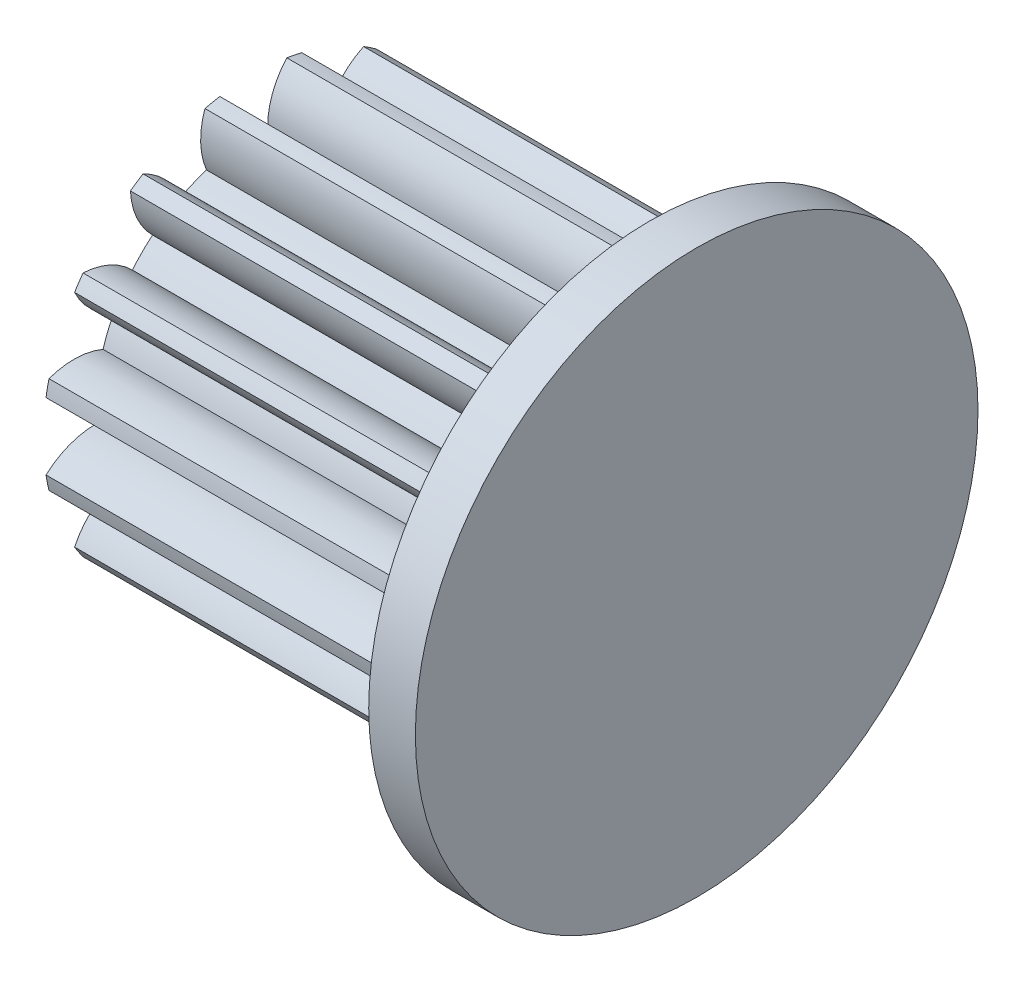
SolidWorks part; units mm, degrees
ref_plane "Plane1" through (0, 0, 0) normal (0, 0, 1) x (1, 0, 0)
ref_plane "Plane2" through (0, 0, 0) normal (0, 1, 0) x (1, 0, 0)
ref_plane "Plane3" through (0, 0, 0) normal (1, 0, 0) x (0, 0, -1)
sketch "HoldingSke" plane through (0, 0, 0) normal (0, 1, 0) x (1, 0, 0)
  line L0 (0, 0) -> (1.9225, -0.5513)
  line L1 (-15, 0) -> (100, 0) construction
  line L2 (0, 0) -> (-2.1039, 2.3779)
  line L3 (0, 0) -> (-11.863, 4.5341)
  line L4 (0, 0) -> (8.3015, 2.3804)
  line L5 (0, 0) -> (-46.8476, -17.4728)
  line L6 (0, 0) -> (-6.2172, -4.1948)
  line L7 (-2.1039, 2.3779) -> (8.6586, 51.2059)
  line L8 (-76.2, 54.61) -> (-75.3, 54.61)
  line L9 (-67.7845, 28.3722) -> (-49.3413, 33.142)
  line L10 (-76.2, 71.12) -> (104.1128, 71.12)
  line L11 (0, 0) -> (-7.5, 0)
  line L12 (-76.2, 101.6) -> (-76.181, 101.6)
  line L13 (24.9733, 27.94) -> (52.9518, 28.4284)
  line L14 (24.9733, 27.94) -> (24.9743, 27.94)
  line L15 (24.9733, 27.94) -> (100.4006, 29.5858)
  line L16 (-63.627, -0.5) -> (-12.827, -0.5)
  circle A0 centre (0, 0) radius 2.5
  circle A1 centre (0, 0) radius 3.374
  circle A2 centre (0, 0) radius 37.5
  circle A3 centre (0, 0) radius 2.5
  dimension "MHD" = 6.748
  dimension "Hub_dia" = 75
  dimension "Bore" = 5
  dimension "MBD" = 5
  dimension "Num_teeth" = 16
  dimension "Pitch" = 2
  dimension "Overall_len" = 50
  dimension "Show_teeth" = 16
  dimension "Thickness" = 7.5
  dimension "OAL" = 50.0001
  dimension "T_dim" = 0.9
  dimension "Ap" = 14.5
  dimension "H" = 19.05
  dimension "Pitch_radius" = 180.3128
  dimension "Width" = 7.5
  dimension "Backlash" = 0.019
  dimension "Addendum_fac" = 1
  dimension "Dedendum_fac" = 1.25
  dimension "Clearance_fac" = 0.25
  dimension "Dedendum_add" = 0.001
  dimension "Module" = 0.5
sketch "BasProSke" plane through (0, 0, 0) normal (0, 1, 0) x (1, 0, 0)
  line L0 (-10, 0) -> (60, 0) construction
  line L1 (0, 0) -> (0, 4.5)
  line L2 (0, 0) -> (7.5, 0)
  line L3 (7.5, 0) -> (7.5, 4.5)
  line L4 (7.5, 4.5) -> (0, 4.5)
  dimension "Thickness" = 7.5
  dimension "Diameter" = 9
revolve "Base-Revolve" add sketch "BasProSke" angle 360 about L0
sketch "TooCutSke" plane through (0, 0, 0) normal (1, 0, 0) x (0, 0, -1)
  line L1 (0, 0) -> (0, 107) construction
  line L2 (0, 0) -> (-0.4253, 3.9773) construction
  line L3 (0, 0) -> (-1.5544, 7.8146) construction
  line L4 (-0.4253, 3.9773) -> (-0.7772, 3.9073) construction
  arc A0 (0.306, 3.3601) -> (-0.306, 3.3601) centre (0, 0) ccw
  arc A1 (0.7382, 4.4648) -> (-0.7382, 4.4648) centre (0, 0) ccw
  circle A2 centre (0, 0) radius 4 construction
  circle A3 centre (0, 0) radius 3.8726 construction
  arc A4 (-0.306, 3.3601) -> (-0.7382, 4.4648) centre (-1.906, 3.3711) ccw
  arc A5 (0.7382, 4.4648) -> (0.306, 3.3601) centre (1.906, 3.3711) ccw
  dimension "Root_dia" = 6.748
  dimension "Overcut_dia" = 9.0508
  dimension "Pitch_dia" = 8
  dimension "Base_dia" = 7.7452
  dimension "Flank_rad" = 1.6
  dimension "Half_ang" = 11.25
  dimension "Half_CT" = 0.3588
extrude "ToothCut" cut sketch "TooCutSke" along normal through all
fillet "Breaks" [suppressed] radius 0.01
fillet "RootFillets" [suppressed] radius 0.126
pattern_circular "TeethCuts" count 16 every 22.5 about axis through (-10, 0, 0) along (1, 0, 0) of "ToothCut", "RootFillets", "Breaks"
sketch "HubNeaOneSke" plane through (0, 0, 0) normal (-1, 0, 0) x (0, 0, 1)
  circle A0 centre (0, 0) radius 3.374
  dimension "Diameter" = 6.748
extrude "HubNearOne" [suppressed] add sketch "HubNeaOneSke" along normal blind 42.5001
sketch "HubNeaBotSke" plane through (0, 0, 0) normal (-1, 0, 0) x (0, 0, 1)
  circle A0 centre (0, 0) radius 3.374
  dimension "Diameter" = 6.748
extrude "HubNearBoth" [suppressed] add sketch "HubNeaBotSke" along normal blind 21.25
ref_plane "FarPln" through (7.5, 0, 0) normal (1, 0, 0) x (0, 0, -1)
sketch "HubFarSke" plane through (7.5, 0, 0) normal (1, 0, 0) x (0, 0, -1)
  circle A0 centre (0, 0) radius 3.374
  dimension "Diameter" = 6.748
extrude "HubFar" [suppressed] add sketch "HubFarSke" along normal blind 21.25
sketch "BorSke" plane through (0, 0, 0) normal (1, 0, 0) x (0, 0, -1)
  circle A0 centre (0, 0) radius 2.5
  dimension "Diameter" = 5
extrude "Bore" cut sketch "BorSke" along normal mid plane 100.0001
sketch "KeySke" plane through (0, 0, 0) normal (1, 0, 0) x (0, 0, -1)
  line L0 (-1, 0) -> (-1, 3.4)
  line L1 (-1, 3.4) -> (1, 3.4)
  line L2 (1, 3.4) -> (1, 0)
  line L3 (0, 0) -> (0, 34) construction
  line L4 (-1, 0) -> (1, 0)
  dimension "Offset" = 3.4
  dimension "Width" = 2
extrude "Keyway" [suppressed] cut sketch "KeySke" along normal mid plane 100.0001
pattern_circular "Keyway2" [suppressed] count 2 every 90 about axis through (-10, 0, 0) along (1, 0, 0)
sketch "Esquisse5" plane through (7.5, 0, 0) normal (1, 0, 0) x (0, 0, -1)
  circle A0 centre (0, 0) radius 2.85
  circle A1 centre (0, 0) radius 6.0278
extrude "Boss.-Extru.4" add sketch "Esquisse5" along normal blind 1
sketch "Esquisse7" plane through (0, 0, 0) normal (-1, 0, 0) x (0, 0, 1)
  circle A0 centre (0, 0) radius 3.0071
extrude "Boss.-Extru.6" add sketch "Esquisse7" along normal up to surface (8.5 mm away)
sketch "Esquisse8" plane through (0, 0, 0) normal (-1, 0, 0) x (0, 0, 1)
  arc A128 (3.3601, 0.306) -> (4.4424, 0.7176) centre (3.3711, 1.906) ccw
  arc A129 (4.4424, 0.7176) -> (4.3789, 1.0371) centre (0, 0) ccw
  arc A130 (4.3789, 1.0371) -> (3.2214, 1.0031) centre (3.8439, -0.4708) ccw
  arc A131 (3.2214, 1.0031) -> (2.9872, 1.5686) centre (0, 0) ccw
  arc A132 (2.9872, 1.5686) -> (3.8296, 2.363) centre (2.3851, 3.051) ccw
  arc A133 (3.8296, 2.363) -> (3.6487, 2.6338) centre (0, 0) ccw
  arc A134 (3.6487, 2.6338) -> (2.5923, 2.1596) centre (3.7314, 1.036) ccw
  arc A135 (2.5923, 2.1596) -> (2.1596, 2.5923) centre (0, 0) ccw
  arc A136 (2.1596, 2.5923) -> (2.6338, 3.6487) centre (1.036, 3.7314) ccw
  arc A137 (2.6338, 3.6487) -> (2.363, 3.8296) centre (0, 0) ccw
  arc A138 (2.363, 3.8296) -> (1.5686, 2.9872) centre (3.051, 2.3851) ccw
  arc A139 (1.5686, 2.9872) -> (1.0031, 3.2214) centre (0, 0) ccw
  arc A140 (1.0031, 3.2214) -> (1.0371, 4.3789) centre (-0.4708, 3.8439) ccw
  arc A141 (1.0371, 4.3789) -> (0.7176, 4.4424) centre (0, 0) ccw
  arc A142 (0.7176, 4.4424) -> (0.306, 3.3601) centre (1.906, 3.3711) ccw
  arc A143 (0.306, 3.3601) -> (-0.306, 3.3601) centre (0, 0) ccw
  arc A144 (-0.306, 3.3601) -> (-0.7176, 4.4424) centre (-1.906, 3.3711) ccw
  arc A145 (-0.7176, 4.4424) -> (-1.0371, 4.3789) centre (0, 0) ccw
  arc A146 (-1.0371, 4.3789) -> (-1.0031, 3.2214) centre (0.4708, 3.8439) ccw
  arc A147 (-1.0031, 3.2214) -> (-1.5686, 2.9872) centre (0, 0) ccw
  arc A148 (-1.5686, 2.9872) -> (-2.363, 3.8296) centre (-3.051, 2.3851) ccw
  arc A149 (-2.363, 3.8296) -> (-2.6338, 3.6487) centre (0, 0) ccw
  arc A150 (-2.6338, 3.6487) -> (-2.1596, 2.5923) centre (-1.036, 3.7314) ccw
  arc A151 (-2.1596, 2.5923) -> (-2.5923, 2.1596) centre (0, 0) ccw
  arc A152 (-2.5923, 2.1596) -> (-3.6487, 2.6338) centre (-3.7314, 1.036) ccw
  arc A153 (-3.6487, 2.6338) -> (-3.8296, 2.363) centre (0, 0) ccw
  arc A154 (-3.8296, 2.363) -> (-2.9872, 1.5686) centre (-2.3851, 3.051) ccw
  arc A155 (-2.9872, 1.5686) -> (-3.2214, 1.0031) centre (0, 0) ccw
  arc A156 (-3.2214, 1.0031) -> (-4.3789, 1.0371) centre (-3.8439, -0.4708) ccw
  arc A157 (-4.3789, 1.0371) -> (-4.4424, 0.7176) centre (0, 0) ccw
  arc A158 (-4.4424, 0.7176) -> (-3.3601, 0.306) centre (-3.3711, 1.906) ccw
  arc A159 (-3.3601, 0.306) -> (-3.3601, -0.306) centre (0, 0) ccw
  arc A160 (-3.3601, -0.306) -> (-4.4424, -0.7176) centre (-3.3711, -1.906) ccw
  arc A161 (-4.4424, -0.7176) -> (-4.3789, -1.0371) centre (0, 0) ccw
  arc A162 (-4.3789, -1.0371) -> (-3.2214, -1.0031) centre (-3.8439, 0.4708) ccw
  arc A163 (-3.2214, -1.0031) -> (-2.9872, -1.5686) centre (0, 0) ccw
  arc A164 (-2.9872, -1.5686) -> (-3.8296, -2.363) centre (-2.3851, -3.051) ccw
  arc A165 (-3.8296, -2.363) -> (-3.6487, -2.6338) centre (0, 0) ccw
  arc A166 (-3.6487, -2.6338) -> (-2.5923, -2.1596) centre (-3.7314, -1.036) ccw
  arc A167 (-2.5923, -2.1596) -> (-2.1596, -2.5923) centre (0, 0) ccw
  arc A168 (-2.1596, -2.5923) -> (-2.6338, -3.6487) centre (-1.036, -3.7314) ccw
  arc A169 (-2.6338, -3.6487) -> (-2.363, -3.8296) centre (0, 0) ccw
  arc A170 (-2.363, -3.8296) -> (-1.5686, -2.9872) centre (-3.051, -2.3851) ccw
  arc A171 (-1.5686, -2.9872) -> (-1.0031, -3.2214) centre (0, 0) ccw
  arc A172 (-1.0031, -3.2214) -> (-1.0371, -4.3789) centre (0.4708, -3.8439) ccw
  arc A173 (-1.0371, -4.3789) -> (-0.7176, -4.4424) centre (0, 0) ccw
  arc A174 (-0.7176, -4.4424) -> (-0.306, -3.3601) centre (-1.906, -3.3711) ccw
  arc A175 (-0.306, -3.3601) -> (0.306, -3.3601) centre (0, 0) ccw
  arc A176 (0.306, -3.3601) -> (0.7176, -4.4424) centre (1.906, -3.3711) ccw
  arc A177 (0.7176, -4.4424) -> (1.0371, -4.3789) centre (0, 0) ccw
  arc A178 (1.0371, -4.3789) -> (1.0031, -3.2214) centre (-0.4708, -3.8439) ccw
  arc A179 (1.0031, -3.2214) -> (1.5686, -2.9872) centre (0, 0) ccw
  arc A180 (1.5686, -2.9872) -> (2.363, -3.8296) centre (3.051, -2.3851) ccw
  arc A181 (2.363, -3.8296) -> (2.6338, -3.6487) centre (0, 0) ccw
  arc A182 (2.6338, -3.6487) -> (2.1596, -2.5923) centre (1.036, -3.7314) ccw
  arc A183 (2.1596, -2.5923) -> (2.5923, -2.1596) centre (0, 0) ccw
  arc A184 (2.5923, -2.1596) -> (3.6487, -2.6338) centre (3.7314, -1.036) ccw
  arc A185 (3.6487, -2.6338) -> (3.8296, -2.363) centre (0, 0) ccw
  arc A186 (3.8296, -2.363) -> (2.9872, -1.5686) centre (2.3851, -3.051) ccw
  arc A187 (2.9872, -1.5686) -> (3.2214, -1.0031) centre (0, 0) ccw
  arc A188 (3.2214, -1.0031) -> (4.3789, -1.0371) centre (3.8439, 0.4708) ccw
  arc A189 (4.3789, -1.0371) -> (4.4424, -0.7176) centre (0, 0) ccw
  arc A190 (4.4424, -0.7176) -> (3.3601, -0.306) centre (3.3711, -1.906) ccw
  arc A191 (3.3601, -0.306) -> (3.3601, 0.306) centre (0, 0) ccw
  arc A192 (3.3601, 0.306) -> (4.4424, 0.7176) centre (3.3711, 1.906) ccw
  arc A193 (4.4424, 0.7176) -> (4.3789, 1.0371) centre (0, 0) ccw
  arc A194 (4.3789, 1.0371) -> (3.2214, 1.0031) centre (3.8439, -0.4708) ccw
  arc A195 (3.2214, 1.0031) -> (2.9872, 1.5686) centre (0, 0) ccw
  arc A196 (2.9872, 1.5686) -> (3.8296, 2.363) centre (2.3851, 3.051) ccw
  arc A197 (3.8296, 2.363) -> (3.6487, 2.6338) centre (0, 0) ccw
  arc A198 (3.6487, 2.6338) -> (2.5923, 2.1596) centre (3.7314, 1.036) ccw
  arc A199 (2.5923, 2.1596) -> (2.1596, 2.5923) centre (0, 0) ccw
  arc A200 (2.1596, 2.5923) -> (2.6338, 3.6487) centre (1.036, 3.7314) ccw
  arc A201 (2.6338, 3.6487) -> (2.363, 3.8296) centre (0, 0) ccw
  arc A202 (2.363, 3.8296) -> (1.5686, 2.9872) centre (3.051, 2.3851) ccw
  arc A203 (1.5686, 2.9872) -> (1.0031, 3.2214) centre (0, 0) ccw
  arc A204 (1.0031, 3.2214) -> (1.0371, 4.3789) centre (-0.4708, 3.8439) ccw
  arc A205 (1.0371, 4.3789) -> (0.7176, 4.4424) centre (0, 0) ccw
  arc A206 (0.7176, 4.4424) -> (0.306, 3.3601) centre (1.906, 3.3711) ccw
  arc A207 (0.306, 3.3601) -> (-0.306, 3.3601) centre (0, 0) ccw
  arc A208 (-0.306, 3.3601) -> (-0.7176, 4.4424) centre (-1.906, 3.3711) ccw
  arc A209 (-0.7176, 4.4424) -> (-1.0371, 4.3789) centre (0, 0) ccw
  arc A210 (-1.0371, 4.3789) -> (-1.0031, 3.2214) centre (0.4708, 3.8439) ccw
  arc A211 (-1.0031, 3.2214) -> (-1.5686, 2.9872) centre (0, 0) ccw
  arc A212 (-1.5686, 2.9872) -> (-2.363, 3.8296) centre (-3.051, 2.3851) ccw
  arc A213 (-2.363, 3.8296) -> (-2.6338, 3.6487) centre (0, 0) ccw
  arc A214 (-2.6338, 3.6487) -> (-2.1596, 2.5923) centre (-1.036, 3.7314) ccw
  arc A215 (-2.1596, 2.5923) -> (-2.5923, 2.1596) centre (0, 0) ccw
  arc A216 (-2.5923, 2.1596) -> (-3.6487, 2.6338) centre (-3.7314, 1.036) ccw
  arc A217 (-3.6487, 2.6338) -> (-3.8296, 2.363) centre (0, 0) ccw
  arc A218 (-3.8296, 2.363) -> (-2.9872, 1.5686) centre (-2.3851, 3.051) ccw
  arc A219 (-2.9872, 1.5686) -> (-3.2214, 1.0031) centre (0, 0) ccw
  arc A220 (-3.2214, 1.0031) -> (-4.3789, 1.0371) centre (-3.8439, -0.4708) ccw
  arc A221 (-4.3789, 1.0371) -> (-4.4424, 0.7176) centre (0, 0) ccw
  arc A222 (-4.4424, 0.7176) -> (-3.3601, 0.306) centre (-3.3711, 1.906) ccw
  arc A223 (-3.3601, 0.306) -> (-3.3601, -0.306) centre (0, 0) ccw
  arc A224 (-3.3601, -0.306) -> (-4.4424, -0.7176) centre (-3.3711, -1.906) ccw
  arc A225 (-4.4424, -0.7176) -> (-4.3789, -1.0371) centre (0, 0) ccw
  arc A226 (-4.3789, -1.0371) -> (-3.2214, -1.0031) centre (-3.8439, 0.4708) ccw
  arc A227 (-3.2214, -1.0031) -> (-2.9872, -1.5686) centre (0, 0) ccw
  arc A228 (-2.9872, -1.5686) -> (-3.8296, -2.363) centre (-2.3851, -3.051) ccw
  arc A229 (-3.8296, -2.363) -> (-3.6487, -2.6338) centre (0, 0) ccw
  arc A230 (-3.6487, -2.6338) -> (-2.5923, -2.1596) centre (-3.7314, -1.036) ccw
  arc A231 (-2.5923, -2.1596) -> (-2.1596, -2.5923) centre (0, 0) ccw
  arc A232 (-2.1596, -2.5923) -> (-2.6338, -3.6487) centre (-1.036, -3.7314) ccw
  arc A233 (-2.6338, -3.6487) -> (-2.363, -3.8296) centre (0, 0) ccw
  arc A234 (-2.363, -3.8296) -> (-1.5686, -2.9872) centre (-3.051, -2.3851) ccw
  arc A235 (-1.5686, -2.9872) -> (-1.0031, -3.2214) centre (0, 0) ccw
  arc A236 (-1.0031, -3.2214) -> (-1.0371, -4.3789) centre (0.4708, -3.8439) ccw
  arc A237 (-1.0371, -4.3789) -> (-0.7176, -4.4424) centre (0, 0) ccw
  arc A238 (-0.7176, -4.4424) -> (-0.306, -3.3601) centre (-1.906, -3.3711) ccw
  arc A239 (-0.306, -3.3601) -> (0.306, -3.3601) centre (0, 0) ccw
  arc A240 (0.306, -3.3601) -> (0.7176, -4.4424) centre (1.906, -3.3711) ccw
  arc A241 (0.7176, -4.4424) -> (1.0371, -4.3789) centre (0, 0) ccw
  arc A242 (1.0371, -4.3789) -> (1.0031, -3.2214) centre (-0.4708, -3.8439) ccw
  arc A243 (1.0031, -3.2214) -> (1.5686, -2.9872) centre (0, 0) ccw
  arc A244 (1.5686, -2.9872) -> (2.363, -3.8296) centre (3.051, -2.3851) ccw
  arc A245 (2.363, -3.8296) -> (2.6338, -3.6487) centre (0, 0) ccw
  arc A246 (2.6338, -3.6487) -> (2.1596, -2.5923) centre (1.036, -3.7314) ccw
  arc A247 (2.1596, -2.5923) -> (2.5923, -2.1596) centre (0, 0) ccw
  arc A248 (2.5923, -2.1596) -> (3.6487, -2.6338) centre (3.7314, -1.036) ccw
  arc A249 (3.6487, -2.6338) -> (3.8296, -2.363) centre (0, 0) ccw
  arc A250 (3.8296, -2.363) -> (2.9872, -1.5686) centre (2.3851, -3.051) ccw
  arc A251 (2.9872, -1.5686) -> (3.2214, -1.0031) centre (0, 0) ccw
  arc A252 (3.2214, -1.0031) -> (4.3789, -1.0371) centre (3.8439, 0.4708) ccw
  arc A253 (4.3789, -1.0371) -> (4.4424, -0.7176) centre (0, 0) ccw
  arc A254 (4.4424, -0.7176) -> (3.3601, -0.306) centre (3.3711, -1.906) ccw
  arc A255 (3.3601, -0.306) -> (3.3601, 0.306) centre (0, 0) ccw
  dimension "D1" = 0
extrude "Boss.-Extru.7" add sketch "Esquisse8" along normal blind 1
sketch "Esquisse9" plane through (-1, 0, 0) normal (-1, 0, 0) x (0, 0, 1)
  circle A0 centre (0, 0) radius 3.25
  dimension "D1" = 6.5
extrude "Enlèv. mat.-Extru.1" cut sketch "Esquisse9" against normal blind 5.5
equation "' \"Module@HoldingSke\" = 6.35"
equation "' \"Num_teeth@HoldingSke\" = 12"
equation "' \"Ap@HoldingSke\" =  20"
equation "' \"Ap@HoldingSke\" = 20"
equation "' \"Width@HoldingSke\" = 0.5 * 25.4"
equation "' \"Hub_dia@HoldingSke\"= 1 * 25.4"
equation "' \"Hub_dia@HoldingSke\" = 1 * 25.4"
equation "' \"Overall_len@HoldingSke\" = 1.0 * 25.4"
equation "' \"Bore@HoldingSke\" = 0.75 * 25.4"
equation "' \"T_dim@HoldingSke\" = 0.1 * 25.4"
equation "' \"Width@KeySke\" = 0.25 * 25.4"
equation "' \"Show_teeth@HoldingSke\" = 13"
equation "' \"Backlash@HoldingSke\" = 0.009 * 25.4"
equation "' \"Addendum_fac@HoldingSke\" = 1.0"
equation "' \"Dedendum_fac@HoldingSke\" = 1.25"
equation "' \"Dedendum_add@HoldingSke\" = 0.00005 * 25.4"
equation "' \"Clearance_fac@HoldingSke\" = 0.25"
equation "\"Pitch@HoldingSke\" = 1 / \"Module@HoldingSke\""
equation "\"Overcut_dia@TooCutSke\" = (\"Num_teeth@HoldingSke\" + 2 * \"Addendum_fac@HoldingSke\") / \"Pitch@HoldingSke\" + 0.002 * 25.4"
equation "\"Pitch_dia@TooCutSke\" = \"Num_teeth@HoldingSke\" / \"Pitch@HoldingSke\""
equation "\"Base_dia@TooCutSke\" = \"Num_teeth@HoldingSke\" / \"Pitch@HoldingSke\" * cos((\"Ap@HoldingSke\"  * 3.14159265 / 180))"
equation "\"Root_dia@TooCutSke\" = (\"Num_teeth@HoldingSke\" + 2) / \"Pitch@HoldingSke\" - 2 * (\"Addendum_fac@HoldingSke\" + \"Dedendum_fac@HoldingSke\") / \"Pitch@HoldingSke\" - \"Dedendum_add@HoldingSke\" * 2"
equation "\"Half_ang@TooCutSke\" = 180 / \"Num_teeth@HoldingSke\""
equation "\"Half_CT@TooCutSke\" = \"Num_teeth@HoldingSke\" / \"Pitch@HoldingSke\" * sin((3.14159265 / 2 / \"Num_teeth@HoldingSke\")) / 2 - 7 * \"Backlash@HoldingSke\" / 4"
equation "\"Flank_rad@TooCutSke\" = \"Num_teeth@HoldingSke\" / \"Pitch@HoldingSke\" / 5"
equation "\"Radius@RootFillets\" = \"Clearance_fac@HoldingSke\" / \"Pitch@HoldingSke\" + \"Dedendum_add@HoldingSke\""
equation "\"Break_rad@Breaks\" = 0.02 / \"Pitch@HoldingSke\""
equation "\"Thickness@HoldingSke\" = \"Width@HoldingSke\""
equation "\"OAL@HoldingSke\" = \"Thickness@HoldingSke\""
equation "\"MHD@HoldingSke\" = (\"Num_teeth@HoldingSke\" + 2) / \"Pitch@HoldingSke\" - 2 * (\"Addendum_fac@HoldingSke\" + \"Dedendum_fac@HoldingSke\")  / \"Pitch@HoldingSke\" - \"Dedendum_add@HoldingSke\" * 2"
equation "\"MBD@HoldingSke\" = (\"Num_teeth@HoldingSke\" + 2) / \"Pitch@HoldingSke\" - 2 * (\"Addendum_fac@HoldingSke\" + \"Dedendum_fac@HoldingSke\")  / \"Pitch@HoldingSke\" - \"Dedendum_add@HoldingSke\" * 2 - 0.002 * 25.4"
equation "\"MHD@HoldingSke\" = ((sgn( \"MHD@HoldingSke\" - \"Hub_dia@HoldingSke\" )-1)*( \"MHD@HoldingSke\" - \"Hub_dia@HoldingSke\" ))/-2+ \"Hub_dia@HoldingSke\""
equation "\"MBD@HoldingSke\" = ((sgn( \"MBD@HoldingSke\" - \"Bore@HoldingSke\" )-1)*( \"MBD@HoldingSke\" - \"Bore@HoldingSke\" ))/-2+ \"Bore@HoldingSke\""
equation "\"OAL@HoldingSke\" = ((sgn( \"OAL@HoldingSke\" - \"Overall_len@HoldingSke\" )+1)*( \"OAL@HoldingSke\" - \"Overall_len@HoldingSke\" ))/2 + \"Overall_len@HoldingSke\" + 0.000002 * 25.4"
equation "\"Num_teeth@TeethCuts\" = int( \"Show_teeth@HoldingSke\" ) + 1"
equation "\"Num_teeth@TeethCuts\" = ((sgn( \"Num_teeth@TeethCuts\" - \"Num_teeth@HoldingSke\" )-1)*( \"Num_teeth@TeethCuts\" - \"Num_teeth@HoldingSke\" ))/-2+ \"Num_teeth@HoldingSke\""
equation "\"Num_teeth@TeethCuts\" = ((sgn( \"Num_teeth@TeethCuts\" - 2.0)+1)*( \"Num_teeth@TeethCuts\" - 2.0))/2 +2.0"
equation "\"Angle@TeethCuts\" = 360.0 / \"Num_teeth@HoldingSke\""
equation "\"Diameter@BasProSke\" = (\"Num_teeth@HoldingSke\" + 2 * \"Addendum_fac@HoldingSke\") / \"Pitch@HoldingSke\""
equation "\"Thickness@BasProSke\"  = \"Thickness@HoldingSke\""
equation "' \"Fillet_rad@BasProSke\" =  \"Thickness@HoldingSke\" * 0.05"
equation "' \"Fillet_rad@BasProSke\" = \"Thickness@HoldingSke\" * 0.05"
equation "\"MHD@HoldingSke\" = ((sgn( \"MHD@HoldingSke\" - \"Root_dia@TooCutSke\" )-1)*( \"MHD@HoldingSke\" - \"Root_dia@TooCutSke\" ))/-2+ \"Root_dia@TooCutSke\""
equation "\"Diameter@HubNeaOneSke\" = \"MHD@HoldingSke\""
equation "\"Length@HubNearOne\" = \"OAL@HoldingSke\" - \"Thickness@BasProSke\""
equation "\"Diameter@HubNeaBotSke\" = \"MHD@HoldingSke\""
equation "\"Length@HubNearBoth\" = ( \"OAL@HoldingSke\" - \"Thickness@BasProSke\" ) / 2.0"
equation "\"Thickness@FarPln\" = \"Thickness@BasProSke\""
equation "\"Diameter@HubFarSke\" = \"MHD@HoldingSke\""
equation "\"Length@HubFar\" = ( \"OAL@HoldingSke\" - \"Thickness@BasProSke\" ) / 2.0"
equation "\"Diameter@BorSke\" = \"MBD@HoldingSke\""
equation "\"D1@Bore\" = \"OAL@HoldingSke\" * 2.0"
equation "\"D1@Keyway\" = \"OAL@HoldingSke\" * 2.0"
equation "\"Offset@KeySke\" = \"T_dim@HoldingSke\" + \"MBD@HoldingSke\" / 2.0"
